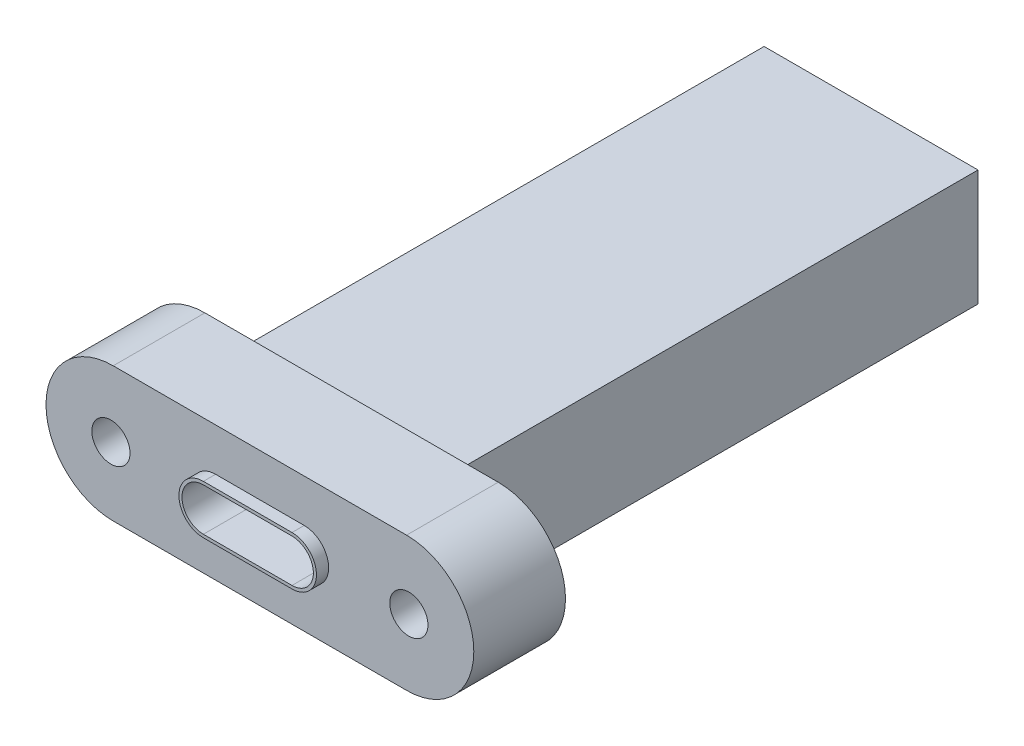
SolidWorks part; units mm, degrees
ref_plane "前视基准面" through (0, 0, 0) normal (0, 0, 1) x (1, 0, 0)
ref_plane "上视基准面" through (0, 0, 0) normal (0, 1, 0) x (1, 0, 0)
ref_plane "右视基准面" through (0, 0, 0) normal (1, 0, 0) x (0, 0, -1)
sketch "草图1" plane through (0, 0, 0) normal (0, 0, 1) x (1, 0, 0)
  line L1 (-7, -3.8) -> (7, -3.8)
  line L2 (-7, -3.8) -> (-7, 3.8)
  line L3 (-7, 3.8) -> (7, 3.8)
  line L4 (7, -3.8) -> (7, 3.8)
  line L5 (-7, -3.8) -> (7, 3.8) construction
  line L6 (-7, 3.8) -> (7, -3.8) construction
  point P0 (0, 0)
  dimension "D1" = 14
  dimension "D2" = 7.6
extrude "凸台-拉伸1" add sketch "草图1" along normal blind 34
sketch "草图2" plane through (0, 0, 34) normal (0, 0, 1) x (1, 0, 0)
  line L0 (-9.6, 0) -> (9.6, 0) construction
  line L1 (-9.6, 4.4) -> (9.6, 4.4)
  line L2 (-9.6, -4.4) -> (9.6, -4.4)
  line L3 (0, 0) -> (0, 8.3819) construction
  arc A0 (-9.6, 4.4) -> (-9.6, -4.4) centre (-9.6, 0) ccw
  arc A1 (9.6, -4.4) -> (9.6, 4.4) centre (9.6, 0) ccw
  point P2 (0, 0)
  point P8 (-14, 0)
  point P9 (14, 0)
  dimension "D1" = 8.8
  dimension "D2" = 28
extrude "凸台-拉伸2" add sketch "草图2" along normal blind 6
sketch "草图3" plane through (0, 0, 40) normal (0, 0, 1) x (1, 0, 0)
  line L0 (-2.9, 0) -> (2.9, 0) construction
  line L1 (-2.9, 1.6) -> (2.9, 1.6)
  line L2 (-2.9, -1.6) -> (2.9, -1.6)
  arc A0 (-2.9, 1.6) -> (-2.9, -1.6) centre (-2.9, 0) ccw
  arc A1 (2.9, -1.6) -> (2.9, 1.6) centre (2.9, 0) ccw
  point P2 (0, 0)
  point P8 (-4.5, 0)
  point P9 (4.5, 0)
  dimension "D1" = 3.2
  dimension "D2" = 9
extrude "凸台-拉伸3" add sketch "草图3" along normal blind 0.8
sketch "草图4" plane through (0, 0, 40.8) normal (0, 0, 1) x (1, 0, 0)
  line L4 (-2.9, -1.4) -> (2.9, -1.4)
  line L5 (2.9, 1.4) -> (-2.9, 1.4)
  line L6 (-2.9, -1.4) -> (2.9, -1.4)
  line L7 (2.9, 1.4) -> (-2.9, 1.4)
  arc A4 (-2.9, 1.4) -> (-2.9, -1.4) centre (-2.9, 0) ccw
  arc A5 (2.9, -1.4) -> (2.9, 1.4) centre (2.9, 0) ccw
  arc A6 (-2.9, 1.4) -> (-2.9, -1.4) centre (-2.9, 0) ccw
  arc A7 (2.9, -1.4) -> (2.9, 1.4) centre (2.9, 0) ccw
  dimension "D1" = 0.2
extrude "切除-拉伸1" cut sketch "草图4" against normal blind 5
sketch "草图5" plane through (0, 0, 40) normal (0, 0, 1) x (1, 0, 0)
  line L0 (-9.75, 0) -> (9.75, 0)
  point P4 (0, 0)
  dimension "D1" = 19.5
hole_wizard "M3 螺纹孔1" positions "草图6" profile "草图7" tap size "M3" standard "GB" end condition through all
sketch "草图6" plane through (0, 0, 40) normal (0, 0, 1) x (1, 0, 0)
  point P0 (-9.75, 0)
  point P3 (9.75, 0)
sketch "草图7" plane through (-9.75, 0, 40) normal (1, 0, 0) x (0, -1, 0)
  line L0 (0, 0) -> (0, 40)
  line L1 (0, 40) -> (1.25, 40)
  line L2 (1.25, 40) -> (1.25, 0)
  line L5 (1.25, 0) -> (0, 0)
  line L11 (0, -6.35) -> (0, 107.95) construction
  dimension "通孔螺纹孔钻头直径" = 2.5
  dimension "通孔螺纹孔钻头深度" = 40
cosmetic thread "孔螺蚊线1" parameters "D2"=3
cosmetic thread "孔螺蚊线2" parameters "D2"=3
